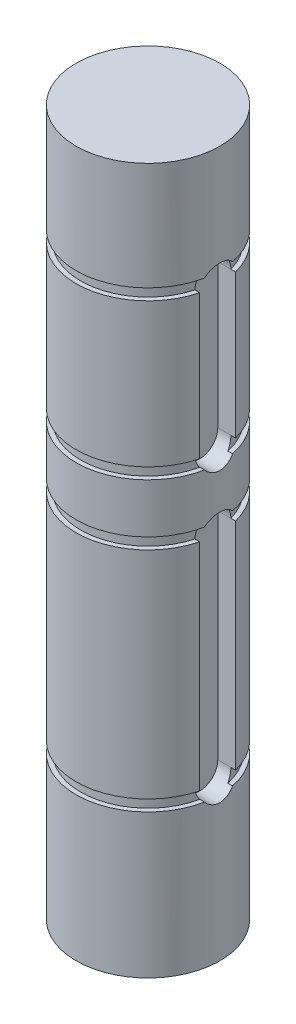
SolidWorks part; units mm, degrees
ref_plane "Front Plane" through (0, 0, 0) normal (0, 0, 1) x (1, 0, 0)
ref_plane "Top Plane" through (0, 0, 0) normal (0, 1, 0) x (1, 0, 0)
ref_plane "Right Plane" through (0, 0, 0) normal (1, 0, 0) x (0, 0, -1)
sketch "Sketch1" plane through (0, 0, 0) normal (0, 1, 0) x (1, 0, 0)
  circle A0 centre (0, 0) radius 2.5
extrude "Boss-Extrude1" add sketch "Sketch1" along normal blind 24.53 contours A0
sketch "Sketch2" plane through (0, 0, 0) normal (1, 0, 0) x (0, 0, -1)
  line L0 (2.5, 24.53) -> (-2.5, 24.53) construction
  line L1 (-8.6269, 20.78) -> (-2.34, 20.78)
  line L2 (-8.6269, 20.78) -> (-8.6269, 20.39)
  line L3 (-8.6269, 20.39) -> (-2.34, 20.39)
  line L4 (-2.34, 20.78) -> (-2.34, 20.39)
  line L5 (-2.5, 24.53) -> (-2.5, 0) construction
  line L7 (0, 23.1041) -> (0, 18.0911) construction
  point P6 (-2.34, 20.585)
  dimension "D1" = 0.39
  dimension "D2" = 3.75
  dimension "D3" = 0.16
revolve "Cut-Revolve2" cut sketch "Sketch2" angle 360 about L7
sketch "Sketch3" plane through (0, 0, 0) normal (1, 0, 0) x (0, 0, -1)
  line L0 (2.5, 24.53) -> (-2.5, 24.53) construction
  line L1 (-16.9583, 15.39) -> (-2.34, 15.39)
  line L2 (-16.9583, 15.39) -> (-16.9583, 15)
  line L3 (-16.9583, 15) -> (-2.34, 15)
  line L4 (-2.34, 15.39) -> (-2.34, 15)
  line L5 (-2.5, 20.39) -> (-2.5, 0) construction
  line L6 (0, 18.5949) -> (0, 8.6846) construction
  dimension "D1" = 9.14
  dimension "D2" = 0.39
  dimension "D3" = 0.16
revolve "Cut-Revolve3" cut sketch "Sketch3" angle 360 about L6
sketch "Sketch4" plane through (0, 0, 0) normal (1, 0, 0) x (0, 0, -1)
  line L0 (2.5, 24.53) -> (-2.5, 24.53) construction
  line L1 (-12.5023, 13.28) -> (-2.34, 13.28)
  line L2 (-12.5023, 13.28) -> (-12.5023, 12.89)
  line L3 (-12.5023, 12.89) -> (-2.34, 12.89)
  line L4 (-2.34, 13.28) -> (-2.34, 12.89)
  line L5 (-2.5, 15) -> (-2.5, 0) construction
  line L6 (0, 14.5589) -> (0, 12.0102) construction
  dimension "D1" = 11.25
  dimension "D2" = 0.39
  dimension "D3" = 0.16
revolve "Cut-Revolve4" cut sketch "Sketch4" angle 360 about L6
sketch "Sketch5" plane through (0, 0, 0) normal (1, 0, 0) x (0, 0, -1)
  line L0 (2.5, 24.53) -> (-2.5, 24.53) construction
  line L1 (-13.5092, 5.39) -> (-2.34, 5.39)
  line L2 (-13.5092, 5.39) -> (-13.5092, 5)
  line L3 (-13.5092, 5) -> (-2.34, 5)
  line L4 (-2.34, 5.39) -> (-2.34, 5)
  line L5 (-2.5, 12.89) -> (-2.5, 0) construction
  line L6 (0, 6.2645) -> (0, 3.7604) construction
  dimension "D1" = 19.14
  dimension "D2" = 0.39
  dimension "D3" = 0.16
revolve "Cut-Revolve5" cut sketch "Sketch5" angle 360 about L6
ref_plane "Plane1" through (2.5, 0, 0) normal (1, 0, 0) x (0, 0, -1)
sketch "Sketch6" plane through (2.5, 0, 0) normal (1, 0, 0) x (0, 0, -1)
  line L0 (0, 20.39) -> (0, 15.39) construction
  line L1 (2.5, 20.39) -> (-2.5, 20.39) construction
  line L2 (-2.34, 15.39) -> (2.34, 15.39) construction
  line L3 (0.625, 20.39) -> (0.625, 15.39)
  line L4 (-0.625, 20.39) -> (-0.625, 15.39)
  arc A0 (0.625, 20.39) -> (-0.625, 20.39) centre (0, 20.39) ccw
  arc A1 (-0.625, 15.39) -> (0.625, 15.39) centre (0, 15.39) ccw
  point P6 (0, 17.89)
  dimension "D1" = 1.25
extrude "Cut-Extrude1" cut sketch "Sketch6" against normal blind 0.7 contours L4 A1 L3 A0
sketch "Sketch7" plane through (2.5, 0, 0) normal (1, 0, 0) x (0, 0, -1)
  line L0 (0, 12.89) -> (0, 5.39) construction
  line L1 (2.5, 12.89) -> (-2.5, 12.89) construction
  line L2 (-2.34, 5.39) -> (2.34, 5.39) construction
  line L3 (0.625, 12.89) -> (0.625, 5.39)
  line L4 (-0.625, 12.89) -> (-0.625, 5.39)
  arc A0 (0.625, 12.89) -> (-0.625, 12.89) centre (0, 12.89) ccw
  arc A1 (-0.625, 5.39) -> (0.625, 5.39) centre (0, 5.39) ccw
  point P6 (0, 9.14)
extrude "Cut-Extrude2" cut sketch "Sketch7" against normal blind 0.7 contours L4 A1 L3 A0
